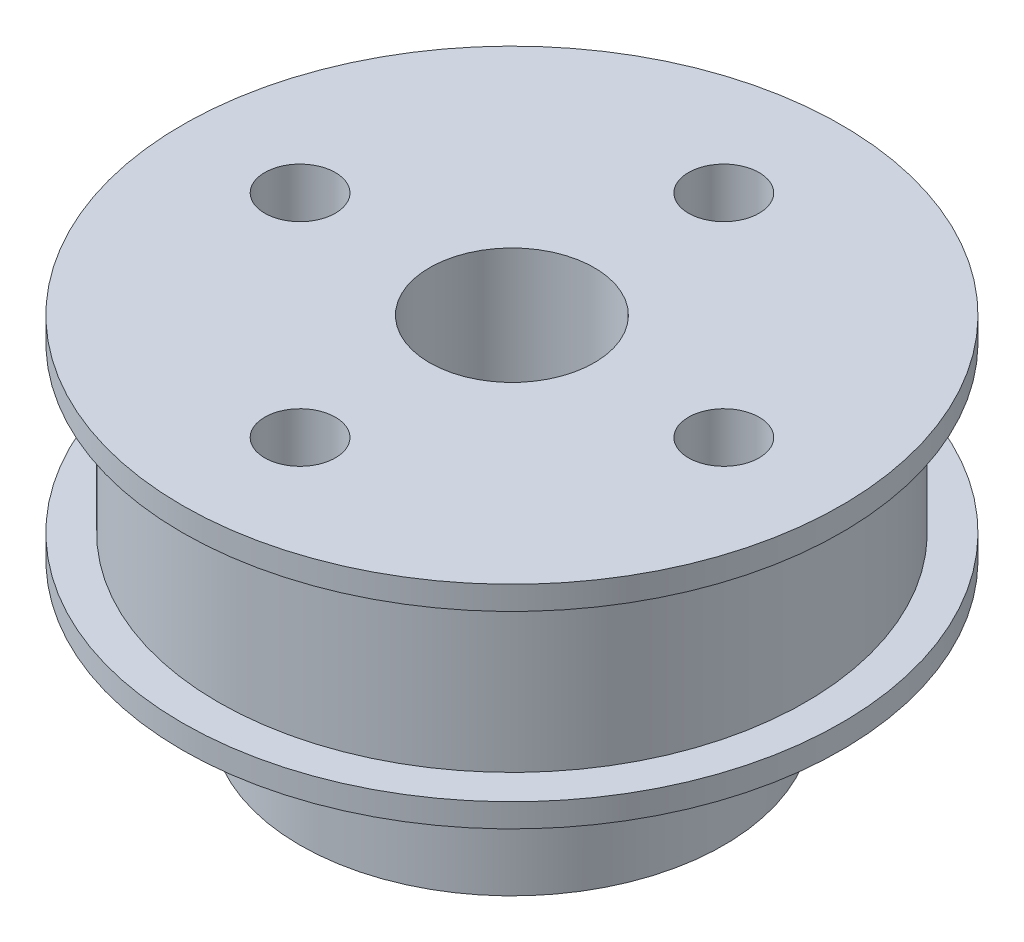
SolidWorks part; units mm, degrees
ref_plane "Front Plane" through (0, 0, 0) normal (0, 0, 1) x (1, 0, 0)
ref_plane "Top Plane" through (0, 0, 0) normal (0, 1, 0) x (1, 0, 0)
ref_plane "Right Plane" through (0, 0, 0) normal (1, 0, 0) x (0, 0, -1)
sketch "Sketch1" plane through (0, 0, 0) normal (0, 1, 0) x (1, 0, 0)
  circle A0 centre (0, 0) radius 14
  dimension "D1" = 28
extrude "Boss-Extrude1" add sketch "Sketch1" along normal blind 1
sketch "Sketch2" plane through (0, 1, 0) normal (0, 1, 0) x (1, 0, 0)
  circle A0 centre (0, 0) radius 12.475
  dimension "D1" = 24.95
extrude "Boss-Extrude2" add sketch "Sketch2" along normal blind 7
sketch "Sketch3" plane through (0, 8, 0) normal (0, 1, 0) x (1, 0, 0)
  circle A0 centre (0, 0) radius 14
  dimension "D1" = 28
extrude "Boss-Extrude3" add sketch "Sketch3" along normal blind 1
sketch "Sketch5" plane through (0, 9, 0) normal (0, 1, 0) x (1, 0, 0)
  circle A0 centre (0, 0) radius 9 construction
  circle A1 centre (0, 9) radius 1.5
  dimension "D1" = 3
  dimension "D2" = 18
extrude "Cut-Extrude2" cut sketch "Sketch5" against normal through all
pattern_circular "CirPattern1" count 4 over 360 about axis through (0, 0, 0) along (0, 1, 0) of "Cut-Extrude2"
sketch "Sketch6" plane through (0, 0, 0) normal (0, -1, 0) x (1, 0, 0)
  circle A0 centre (0, 0) radius 9
  dimension "D1" = 18
extrude "Boss-Extrude4" add sketch "Sketch6" along normal blind 6
sketch "Sketch4" plane through (0, 9, 0) normal (0, 1, 0) x (1, 0, 0)
  circle A0 centre (0, 0) radius 3.5
  dimension "D1" = 7
extrude "Cut-Extrude1" cut sketch "Sketch4" against normal through all
hole_wizard "Ø3.0 (3) Diameter Hole1" positions "3DSketch1" profile "Sketch7" hole size "Ø3.0" standard "ANSI Metric"
sketch3d "3DSketch1"
  point P0 (6.343, -3, -6.3849)
  dimension "D1" = 3
sketch "Sketch7" plane through (6.343, -3, -6.3849) normal (0, 1, 0) x (-0.7094, 0, -0.7048)
  line L0 (0, 0) -> (0, 5.5)
  line L1 (0, 5.5) -> (1.5, 5.5)
  line L2 (1.5, 5.5) -> (1.5, 0)
  line L5 (1.5, 0) -> (0, 0)
  line L11 (0, -6.35) -> (0, 107.95) construction
  dimension "Thru Hole Dia." = 3
  dimension "Thru Hole Depth" = 5.5
